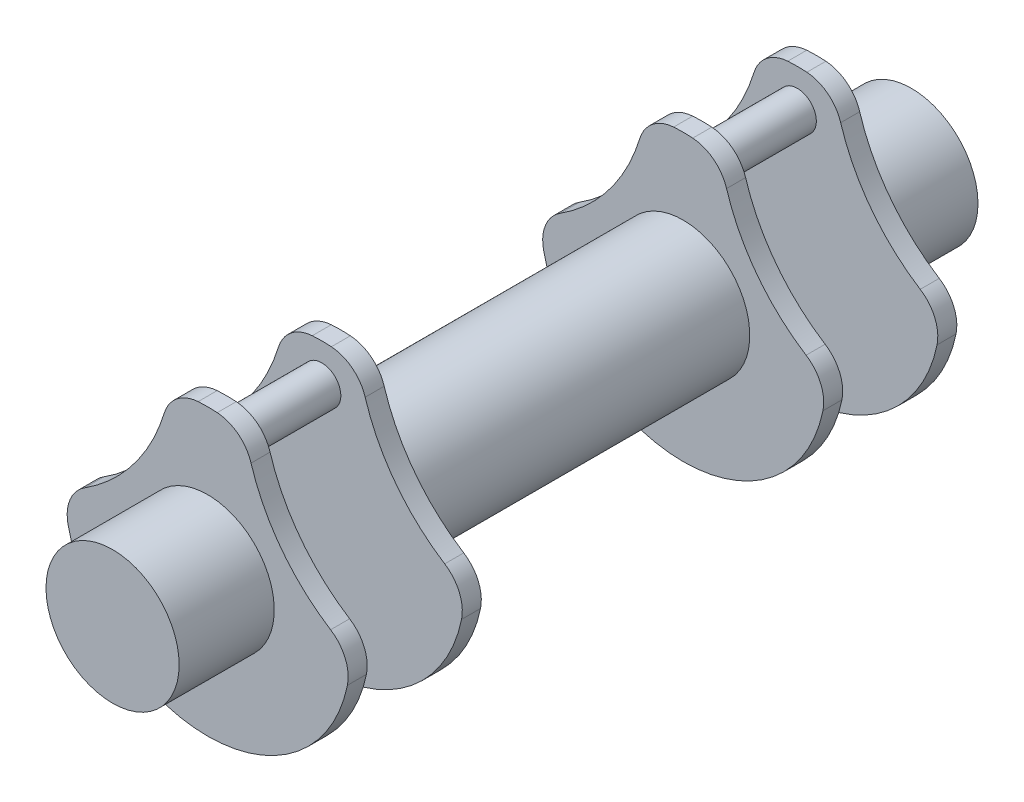
SolidWorks part; units mm, degrees
ref_plane "Front Plane" through (0, 0, 0) normal (0, 0, 1) x (1, 0, 0)
ref_plane "Top Plane" through (0, 0, 0) normal (0, 1, 0) x (1, 0, 0)
ref_plane "Right Plane" through (0, 0, 0) normal (1, 0, 0) x (0, 0, -1)
sketch "Sketch1" plane through (0, 0, 0) normal (0, 0, 1) x (1, 0, 0)
  line L0 (0, 0) -> (0, 255.3016) construction
  arc A0 (20, 72.2842) -> (-20, 72.2842) centre (0, 0) ccw
  arc A1 (-75, 0) -> (-20, 72.2842) centre (-118.4019, 90.0904) ccw
  arc A2 (75, 0) -> (20, 72.2842) centre (118.4019, 90.0904) cw
  arc A3 (-75, 0) -> (75, 0) centre (0, 0) ccw
  dimension "D1" = 75
  dimension "D2" = 100
  dimension "D3" = 40
extrude "Boss-Extrude1" add sketch "Sketch1" along normal blind 10
fillet "Fillet1" radius 20 4 edges at (75, 0, 5) (-75, 0, 5) (-20, 72.2842, 5) (20, 72.2842, 5)
move or copy body "Body-Move/Copy1" bodies to move or copy 101 copy yes number of copies 1 translate (0, 0, 60)
sketch "Sketch2" plane through (0, 0, 10) normal (0, 0, 1) x (1, 0, 0)
  line L0 (0, 55) -> (0, 75) construction
  circle A0 centre (0, 55) radius 10
  arc A1 (5.025, 74.8315) -> (-5.025, 74.8315) centre (0, 0) ccw construction
  dimension "D2" = 20
  dimension "D1" = 20
extrude "Boss-Extrude2" add sketch "Sketch2" along normal up to next
move or copy body "Body-Move/Copy2" bodies to move or copy 103 copy yes number of copies 1 translate (0, 0, -250)
sketch "Sketch3" plane through (0, 0, -180) normal (0, 0, 1) x (1, 0, 0)
  circle A0 centre (0, 0) radius 35
  dimension "D1" = 70
extrude "Boss-Extrude3" add sketch "Sketch3" along normal up to next
sketch "Sketch4" plane through (0, 0, 70) normal (0, 0, 1) x (1, 0, 0)
  circle A0 centre (0, 0) radius 35 construction
  circle A1 centre (0, 0) radius 35
extrude "Boss-Extrude4" add sketch "Sketch4" along normal blind 50
ref_plane "Plane1" through (0, 0, -90) normal (0, 0, 1) x (1, 0, 0)
mirror "Mirror1" about plane through (0, 0, -90) normal (0, 0, 1) of "Boss-Extrude4"
